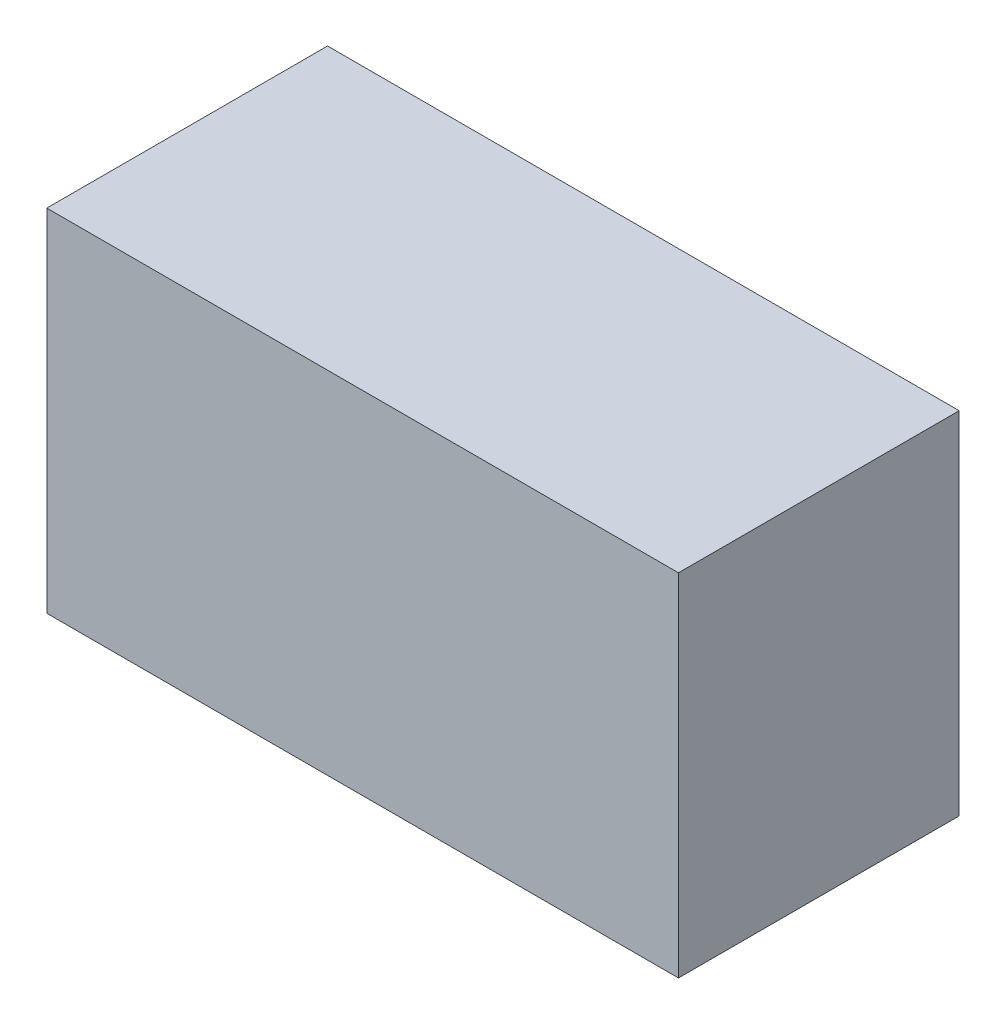
SolidWorks part; units mm, degrees
ref_plane "Front Plane" through (0, 0, 0) normal (0, 0, 1) x (1, 0, 0)
ref_plane "Top Plane" through (0, 0, 0) normal (0, 1, 0) x (1, 0, 0)
ref_plane "Right Plane" through (0, 0, 0) normal (1, 0, 0) x (0, 0, -1)
sketch "Sketch1" plane through (0, 0, 0) normal (0, 1, 0) x (1, 0, 0)
  line L1 (-22.5, 10) -> (22.5, 10)
  line L2 (-22.5, 10) -> (-22.5, -10)
  line L3 (-22.5, -10) -> (22.5, -10)
  line L4 (22.5, 10) -> (22.5, -10)
  line L5 (-22.5, 10) -> (22.5, -10) construction
  line L6 (-22.5, -10) -> (22.5, 10) construction
  point P0 (0, 0)
  dimension "D1" = 20
  dimension "D2" = 45
extrude "Boss-Extrude1" add sketch "Sketch1" along normal blind 25
